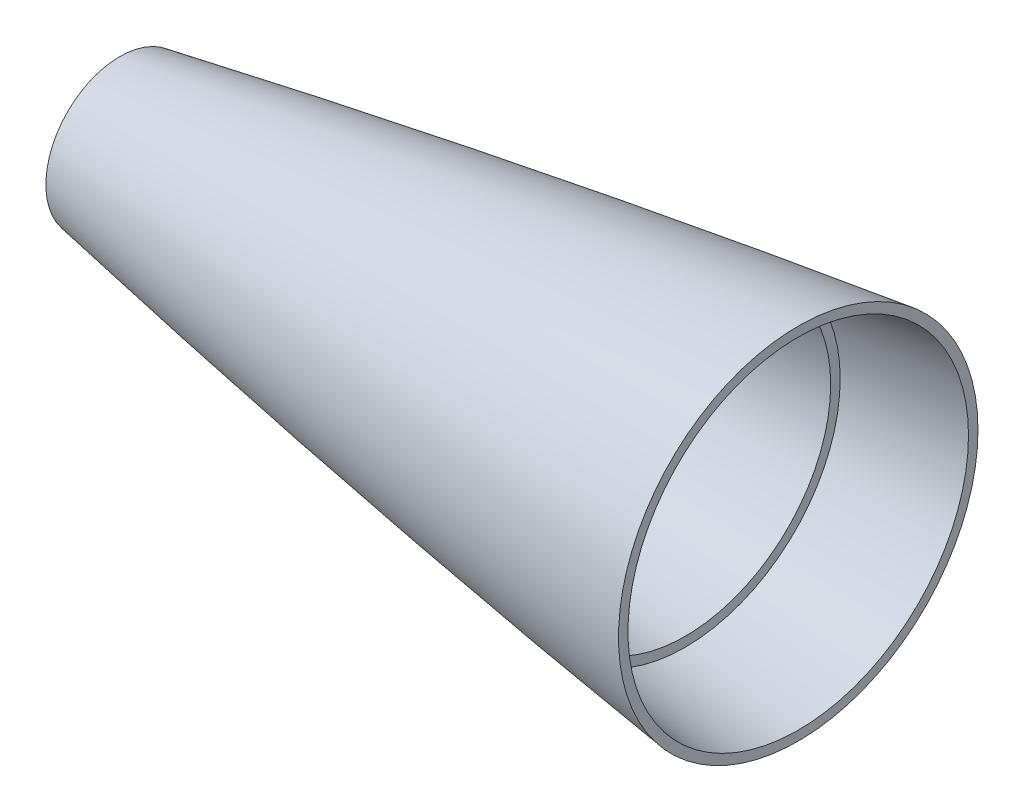
SolidWorks part; units mm, degrees
material "Thornel Mat VMA"
ref_plane "Front Plane" through (0, 0, 0) normal (0, 0, 1) x (1, 0, 0)
ref_plane "Top Plane" through (0, 0, 0) normal (0, 1, 0) x (1, 0, 0)
ref_plane "Right Plane" through (0, 0, 0) normal (1, 0, 0) x (0, 0, -1)
sketch "Sketch1" plane through (0, 0, 0) normal (0, 0, 1) x (1, 0, 0)
  line L0 (0, 0) -> (0, 3483.1) construction
  line L1 (0, 3635.5) -> (0, 3632.5)
  line L2 (0, 3557.2968) -> (-750, 3557.2968) construction
  line L3 (0, 3632.5) -> (0, 3635.5) construction
  line L4 (0, 3632.5) -> (160, 3632.5)
  line L5 (-5, 3627.5) -> (160, 3627.5)
  line L6 (-5, 3630.4966) -> (-5, 3627.5)
  line L7 (-750, 3557.2968) -> (-725.3758, 3557.2968)
  line L8 (160, 3632.5) -> (160, 3627.5)
  line L9 (-650, 3576.9205) -> (-650, 3571.8385)
  line L10 (-650, 3571.8385) -> (-600, 3571.8385)
  line L11 (-600, 3571.8385) -> (-600, 3580.5768)
  line L12 (-2.5, 3630) -> (157.5, 3630) construction
  line L13 (-2.5, 3630) -> (157.5, 3630) construction
  line L14 (-725.628, 3559.7968) -> (-725.628, 3559.7968)
  line L15 (-500, 3598.4287) -> (-500, 3595.9046)
  line L18 (157.5, 3630) -> (157.5, 3630)
  line L21 (-2.5, 3632.9991) -> (-2.5, 3630) construction
  line L22 (-2.5, 3632.9991) -> (-2.5, 3630) construction
  line L23 (-470, 3604.991) -> (-470, 3602.4698)
  line L24 (-320, 3621.3893) -> (-320, 3618.8795)
  line L25 (-350, 3616.1014) -> (-350, 3613.5897)
  line L26 (-40, 3632.7798) -> (-40, 3630.2796)
  line L27 (-10, 3632.9862) -> (-10, 3635.4862)
  line L28 (-170, 3629.0204) -> (-170, 3631.5231)
  line L29 (-200, 3627.4907) -> (-200, 3624.9869)
  line L30 (-40, 3630.2796) -> (-40, 3627.5)
  line L31 (-40, 3627.5) -> (-5, 3627.5)
  line L32 (-10, 3632.9862) -> (-10, 3632.6862)
  line L33 (-170, 3629.0204) -> (-170, 3628.7201)
  line L34 (-320, 3618.8795) -> (-320, 3618.5784)
  line L35 (-470, 3602.4698) -> (-470, 3602.1673)
  arc A0 (0, 3635.5) -> (-750, 3557.2968) centre (0, 0) ccw
  arc A1 (-5, 3630.4966) -> (-600, 3580.5768) centre (0, 0) ccw
  arc A2 (-5, 3630.4966) -> (-748.9685, 3552.4043) centre (0, 0) ccw construction
  arc A5 (-650, 3571.8385) -> (-725.3758, 3557.2968) centre (0, 0) ccw
  arc A6 (-5, 3630.4966) -> (-725.3758, 3557.2968) centre (0, 0) ccw construction
  arc A7 (-2.5, 3632.9991) -> (-725.628, 3559.7968) centre (0, 0) ccw construction
  arc A8 (-2.5, 3632.9991) -> (-725.628, 3559.7968) centre (0, 0) ccw construction
  arc A9 (-500, 3598.4287) -> (-470, 3602.4698) centre (0, 0) cw
  arc A10 (-350, 3616.1014) -> (-320, 3618.8795) centre (0, 0) cw
  arc A11 (-10, 3632.9862) -> (-40, 3632.7798) centre (0, 0) ccw
  arc A12 (-170, 3629.0204) -> (-200, 3627.4907) centre (0, 0) ccw
  arc A13 (-40, 3632.4798) -> (-10, 3632.6862) centre (0, 0) cw
  arc A14 (-200, 3627.1903) -> (-170, 3628.7201) centre (0, 0) cw
  arc A15 (-350, 3615.8) -> (-320, 3618.5784) centre (0, 0) cw
  arc A16 (-500, 3598.1258) -> (-470, 3602.1673) centre (0, 0) cw
  dimension "D1" = 7271
  dimension "D7" = 100
  dimension "D10" = 30
  dimension "D8" = 3633
  dimension "D12" = 3633
  dimension "D15" = 3633
  dimension "D18" = 3633
  dimension "D21" = 3632.7
  dimension "D23" = 3632.7
  dimension "D22" = 3632.7
  dimension "D24" = 3632.7
  dimension "D2" = 152.4
  dimension "D3" = 750
  dimension "D4" = 3
  dimension "D5" = 160
  dimension "D9" = 50
  dimension "D11" = 180
  dimension "D13" = 30
  dimension "D14" = 180
  dimension "D16" = 30
  dimension "D17" = 200
  dimension "D19" = 30
  dimension "D20" = 180
  dimension "D6" = 5
revolve "Revolve1" add sketch "Sketch1" angle 360 about L2
